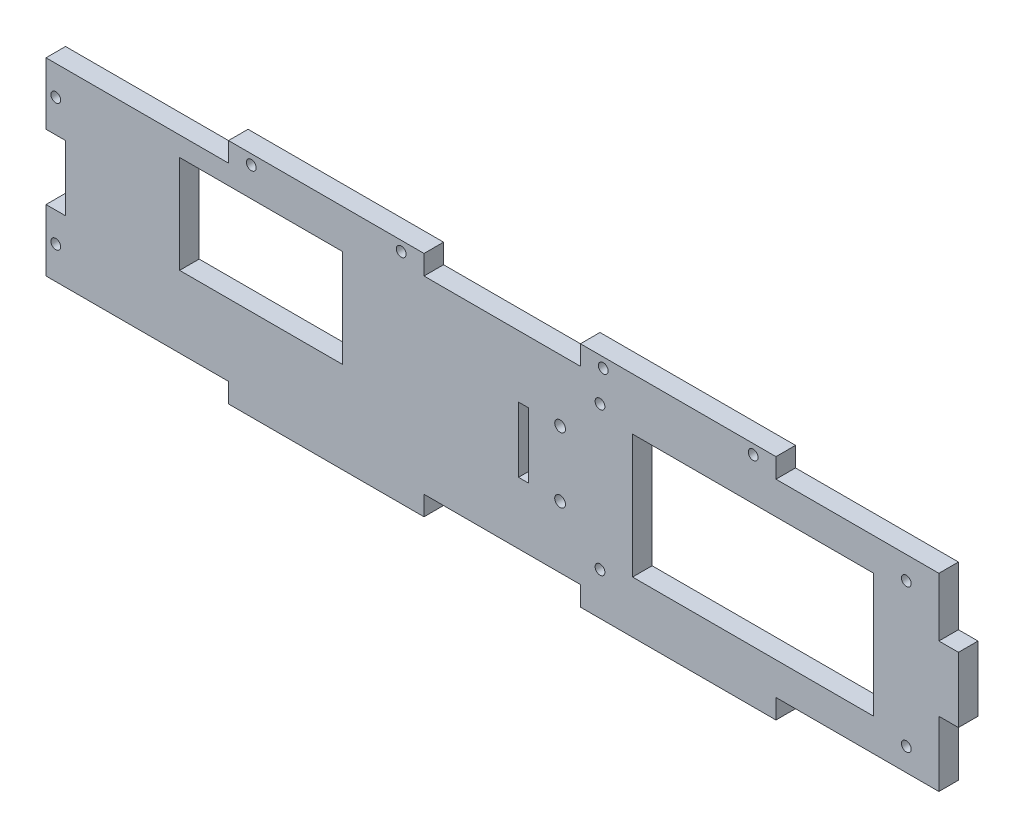
SolidWorks part; units mm, degrees
ref_plane "Plan de face" through (0, 0, 0) normal (0, 0, 1) x (1, 0, 0)
ref_plane "Plan de dessus" through (0, 0, 0) normal (0, 1, 0) x (1, 0, 0)
ref_plane "Plan de droite" through (0, 0, 0) normal (1, 0, 0) x (0, 0, -1)
sketch "Esquisse1" plane through (0, 0, 0) normal (0, 0, 1) x (1, 0, 0)
  line L1 (0, 0) -> (-268, 0)
  line L2 (0, 0) -> (0, 70)
  line L3 (0, 70) -> (-268, 70)
  line L4 (-268, 0) -> (-268, 70)
  dimension "D1" = 70
  dimension "D2" = 268
extrude "Boss.-Extru.1" add sketch "Esquisse1" along normal blind 6
sketch "Esquisse2" plane through (0, 0, 6) normal (0, 0, 1) x (1, 0, 0)
  line L0 (-268, 0) -> (0, 0) construction
  line L1 (-268, 0) -> (-218, 0)
  line L2 (-268, 0) -> (-268, 6)
  line L3 (-268, 6) -> (-218, 6)
  line L4 (-218, 0) -> (-218, 6)
  line L5 (0, 0) -> (-50, 0)
  line L6 (0, 0) -> (0, 6)
  line L7 (0, 6) -> (-50, 6)
  line L8 (-50, 0) -> (-50, 6)
  line L9 (-158, 0) -> (-110, 0)
  line L10 (-158, 0) -> (-158, 6)
  line L11 (-158, 6) -> (-110, 6)
  line L12 (-110, 0) -> (-110, 6)
  line L13 (0, 70) -> (-268, 70) construction
  line L14 (-268, 70) -> (-218, 70)
  line L15 (-268, 70) -> (-268, 64)
  line L16 (-268, 64) -> (-218, 64)
  line L17 (-218, 70) -> (-218, 64)
  line L18 (-158, 70) -> (-110, 70)
  line L19 (-158, 70) -> (-158, 64)
  line L20 (-158, 64) -> (-110, 64)
  line L21 (-110, 70) -> (-110, 64)
  line L23 (0, 70) -> (-50, 70)
  line L24 (0, 70) -> (0, 64)
  line L25 (0, 64) -> (-50, 64)
  line L26 (-50, 70) -> (-50, 64)
  dimension "D1" = 6
  dimension "D2" = 6
  dimension "D3" = 6
  dimension "D4" = 50
  dimension "D5" = 60
  dimension "D6" = 60
  dimension "D7" = 50
  dimension "D8" = 6
  dimension "D9" = 6
  dimension "D10" = 6
  dimension "D11" = 50
  dimension "D12" = 60
  dimension "D13" = 50
  dimension "D14" = 60
extrude "Enlèv. mat.-Extru.1" cut sketch "Esquisse2" against normal through all
sketch "Esquisse3" plane through (0, 0, 0) normal (1, 0, 0) x (0, 0, -1)
  line L0 (-6, 6) -> (-6, 64) construction
  line L1 (-6, 46) -> (0, 46)
  line L2 (-6, 46) -> (-6, 26)
  line L3 (-6, 26) -> (0, 26)
  line L4 (0, 46) -> (0, 26)
  line L5 (0, 6) -> (0, 64) construction
  line L8 (0, 6) -> (-6, 6) construction
  dimension "D1" = 20
  dimension "D2" = 20
extrude "Boss.-Extru.2" add sketch "Esquisse3" along normal blind 6
sketch "Esquisse4" plane through (0, 0, 6) normal (0, 0, 1) x (1, 0, 0)
  line L0 (-218, 6) -> (-268, 6) construction
  line L2 (0, 46) -> (0, 64) construction
  line L3 (-94, 54) -> (-20, 54)
  line L4 (-94, 54) -> (-94, 16)
  line L5 (-94, 16) -> (-20, 16)
  line L6 (-20, 54) -> (-20, 16)
  line L7 (-110, 6) -> (-158, 6) construction
  line L8 (-129, 25) -> (-126, 25)
  line L9 (-129, 25) -> (-129, 45)
  line L10 (-129, 45) -> (-126, 45)
  line L11 (-126, 25) -> (-126, 45)
  line L12 (0, 46) -> (0, 64) construction
  line L13 (0, 6) -> (-50, 6) construction
  line L15 (-158, 70) -> (-218, 70) construction
  line L16 (-183, 58) -> (-233, 58)
  line L17 (-183, 58) -> (-183, 28)
  line L18 (-183, 28) -> (-233, 28)
  line L19 (-233, 58) -> (-233, 28)
  line L21 (-268, 64) -> (-268, 6) construction
  circle A0 centre (-104, 57) radius 1.5
  circle A1 centre (-104, 13) radius 1.5
  circle A2 centre (-10, 57) radius 1.5
  circle A3 centre (-10, 13) radius 1.5
  dimension "D1" = 44
  dimension "D16" = 7
  dimension "D10" = 38
  dimension "D2" = 94
  dimension "D3" = 0
  dimension "D4" = 0
  dimension "D5" = 7
  dimension "D6" = 10
  dimension "D7" = 0
  dimension "D8" = 10
  dimension "D9" = 74
  dimension "D11" = 20
  dimension "D12" = 3
  dimension "D13" = 19
  dimension "D14" = 126
  dimension "D15" = 20
  dimension "D17" = 35
  dimension "D18" = 50
  dimension "D19" = 30
  dimension "D20" = 12
extrude "Enlèv. mat.-Extru.2" cut sketch "Esquisse4" against normal blind 10
sketch "Esquisse5" plane through (-268, 0, 0) normal (-1, 0, 0) x (0, 0, 1)
  line L0 (6, 64) -> (6, 6) construction
  line L1 (0, 64) -> (6, 64)
  line L2 (0, 64) -> (0, 45)
  line L3 (0, 45) -> (6, 45)
  line L4 (6, 64) -> (6, 45)
  line L5 (0, 64) -> (0, 6) construction
  line L6 (6, 6) -> (0, 6)
  line L7 (6, 6) -> (6, 25)
  line L8 (6, 25) -> (0, 25)
  line L9 (0, 6) -> (0, 25)
  dimension "D1" = 20
  dimension "D2" = 19
extrude "Boss.-Extru.3" add sketch "Esquisse5" along normal blind 6
sketch "Esquisse6" plane through (0, 0, 0) normal (0, 0, -1) x (-1, 0, 0)
  line L0 (274, 25) -> (274, 6) construction
  line L1 (218, 6) -> (274, 6) construction
  line L2 (274, 64) -> (274, 45) construction
  line L3 (274, 45) -> (268, 45) construction
  line L4 (158, 70) -> (218, 70) construction
  line L5 (218, 64) -> (218, 70) construction
  line L6 (158, 70) -> (158, 64) construction
  line L7 (110, 64) -> (110, 70) construction
  line L8 (50, 70) -> (110, 70) construction
  line L9 (50, 70) -> (50, 64) construction
  circle A0 centre (271, 16) radius 1.5
  circle A1 centre (271, 55) radius 1.5
  circle A2 centre (211, 67) radius 1.5
  circle A3 centre (165, 67) radius 1.5
  circle A4 centre (103, 67) radius 1.5
  circle A5 centre (57, 67) radius 1.5
  point P22 (218, 67)
  point P25 (158, 67)
  dimension "D1" = 3
  dimension "D2" = 3
  dimension "D3" = 10
  dimension "D4" = 3
  dimension "D5" = 3
  dimension "D6" = 10
  dimension "D7" = 3
  dimension "D8" = 3
  dimension "D9" = 7
  dimension "D10" = 3
  dimension "D11" = 7
  dimension "D12" = 3
  dimension "D13" = 7
  dimension "D14" = 3
  dimension "D15" = 3
  dimension "D16" = 3
  dimension "D17" = 3
  dimension "D18" = 7
extrude "Enlèv. mat.-Extru.3" cut sketch "Esquisse6" against normal through all
sketch "Esquisse7" plane through (0, 0, 0) normal (0, 0, -1) x (-1, 0, 0)
  circle A0 centre (271, 16) radius 2.995
  circle A1 centre (271, 55) radius 2.995
  circle A2 centre (211, 67) radius 2.995
  circle A3 centre (165, 67) radius 2.995
  circle A4 centre (103, 67) radius 2.995
  circle A5 centre (57, 67) radius 2.995
  circle A6 centre (104, 57) radius 3
  circle A7 centre (104, 13) radius 3
  circle A8 centre (10, 13) radius 3
  circle A9 centre (10, 57) radius 3
  dimension "D1" = 6
  dimension "D2" = 5.99
  dimension "D3" = 5.99
  dimension "D4" = 5.99
  dimension "D5" = 5.99
  dimension "D6" = 5.99
  dimension "D7" = 5.99
  dimension "D8" = 6
  dimension "D9" = 6
  dimension "D10" = 6
extrude "Enlèv. mat.-Extru.4" cut sketch "Esquisse7" against normal blind 3
sketch "Esquisse8" plane through (0, 0, 0) normal (0, 0, -1) x (-1, 0, 0)
  line L0 (110, 6) -> (158, 6) construction
  circle A0 centre (116.2423, 25) radius 1.65
  circle A1 centre (116.2423, 45) radius 1.65
  dimension "D1" = 3.3
  dimension "D2" = 3.3
  dimension "D4" = 19
  dimension "D3" = 20
extrude "Enlèv. mat.-Extru.5" cut sketch "Esquisse8" against normal through all
